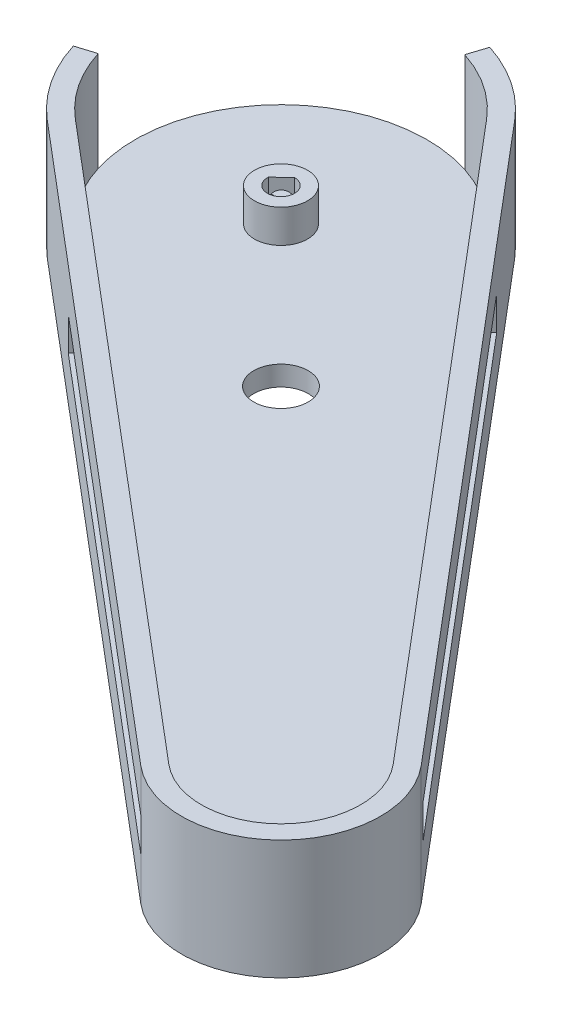
SolidWorks part; units mm, degrees
ref_plane "前视基准面" through (0, 0, 0) normal (0, 0, 1) x (1, 0, 0)
ref_plane "上视基准面" through (0, 0, 0) normal (0, 1, 0) x (1, 0, 0)
ref_plane "右视基准面" through (0, 0, 0) normal (1, 0, 0) x (0, 0, -1)
other "Configuration Table"
sketch "草图2" plane through (0, 0, 0) normal (0, 1, 0) x (1, 0, 0)
  line L0 (-140.5033, 0) -> (6884.6605, 0) construction
  line L1 (0, -140.5033) -> (0, 6884.6605) construction
  line L2 (0, 0) -> (42.4264, -42.4264)
  line L3 (42.4264, -42.4264) -> (-42.4264, 42.4264)
  line L4 (-58.5694, 23.3371) -> (32.7406, -53.88)
  line L5 (-23.3371, 58.5694) -> (53.88, -32.7406)
  circle A0 centre (-42.4264, 42.4264) radius 25
  circle A1 centre (42.4264, -42.4264) radius 15
  dimension "D3" = 50
  dimension "D4" = 30
  dimension "D1" = 60
  dimension "D2" = 120
extrude "凸台-拉伸2" add sketch "草图2" along normal blind 3
sketch "草图4" plane through (0, 3, 0) normal (0, 1, 0) x (1, 0, 0)
  line L0 (-58.5694, 23.3371) -> (32.7406, -53.88)
  line L1 (-58.5694, 23.3371) -> (32.7406, -53.88) construction
  line L2 (-23.3371, 58.5694) -> (53.88, -32.7406)
  line L3 (-23.3371, 58.5694) -> (53.88, -32.7406) construction
  line L4 (-56.6323, 25.6278) -> (34.6777, -51.5893)
  line L5 (-25.6278, 56.6323) -> (51.5893, -34.6777)
  circle A0 centre (-42.4264, 42.4264) radius 25
  circle A1 centre (42.4264, -42.4264) radius 15
  circle A2 centre (-42.4264, 42.4264) radius 22
  circle A3 centre (42.4264, -42.4264) radius 12
  circle A4 centre (-42.4264, 42.4264) radius 2.25
  circle A5 centre (42.4264, -42.4264) radius 2.5
  dimension "D3" = 4.5
  dimension "D4" = 5
  dimension "D1" = 3
  dimension "D2" = 3
extrude "切除-拉伸2" cut sketch "草图4" against normal through all contours A4 | A5
sketch "草图6" plane through (0, 3, 0) normal (0, 1, 0) x (1, 0, 0)
  circle A0 centre (-42.4264, 42.4264) radius 3.5
  dimension "D1" = 7
extrude "切除-拉伸3" cut sketch "草图6" against normal through all
sketch "草图7" plane through (0, 3, 0) normal (0, 1, 0) x (1, 0, 0)
  circle A0 centre (42.4264, -42.4264) radius 3.5
  dimension "D1" = 7
extrude "切除-拉伸4" cut sketch "草图7" against normal through all
sketch "草图8" plane through (0, 3, 0) normal (0, 1, 0) x (1, 0, 0)
  line L0 (-11.8521, 30.3069) -> (-26.8914, 12.9805)
  line L1 (-26.8914, 12.9805) -> (25.2188, -32.2512)
  line L2 (25.2188, -32.2512) -> (33.6267, -22.5647)
  line L3 (33.6267, -22.5647) -> (-15.703, 25.8704)
extrude "切除-拉伸5" cut sketch "草图8" against normal through all contours L2 L3 L0 L1
sketch "草图9" plane through (0, 3, 0) normal (0, 1, 0) x (1, 0, 0)
  line L0 (-23.3371, 58.5694) -> (53.88, -32.7406)
  line L1 (-58.5694, 23.3371) -> (32.7406, -53.88)
  line L2 (-56.6323, 25.6278) -> (34.6777, -51.5893)
  line L3 (-25.6278, 56.6323) -> (51.5893, -34.6777)
  circle A0 centre (-42.4264, 42.4264) radius 25
  circle A1 centre (42.4264, -42.4264) radius 15
  circle A2 centre (-42.4264, 42.4264) radius 22
  circle A3 centre (42.4264, -42.4264) radius 12
  line M8 (-58.5694, 23.3371) -> (32.7406, -53.88)
  arc M9 (32.7406, -53.88) -> (53.88, -32.7406) centre (42.4264, -42.4264) ccw
  line M10 (53.88, -32.7406) -> (-23.3371, 58.5694)
  arc M11 (-23.3371, 58.5694) -> (-58.5694, 23.3371) centre (-42.4264, 42.4264) ccw
  dimension "D1" = 3
  dimension "D2" = 3
extrude "凸台-拉伸4" add sketch "草图9" along normal blind 15 contours A2 L3 A0 L2 M11 | A1 A0 L3 M10 | A1 L2 A0 M8 | A3 L2 A1 L3 M9
sketch "草图10" plane through (0, 3, 0) normal (0, 1, 0) x (1, 0, 0)
  line L0 (-42.4264, 42.4264) -> (42.4264, -42.4264)
  line L1 (42.4264, -42.4264) -> (10.5288, -10.5288)
  line L2 (-26.8914, 12.9805) -> (-15.703, 25.8704)
  line L3 (-15.703, 25.8704) -> (33.6267, -22.5647)
  line L4 (33.6267, -22.5647) -> (25.2188, -32.2512)
  line L5 (25.2188, -32.2512) -> (-26.8914, 12.9805)
  line M5 (33.6267, -22.5647) -> (25.2188, -32.2512)
  line M6 (25.2188, -32.2512) -> (-26.8914, 12.9805)
  line M7 (-26.8914, 12.9805) -> (-15.703, 25.8704)
  line M8 (-15.703, 25.8704) -> (33.6267, -22.5647)
extrude "凸台-拉伸5" add sketch "草图10" against normal blind 3 contours L0 M7 M6 M5 | L0 M7 M5 M8
sketch "草图11" plane through (0, 3, 0) normal (0, 1, 0) x (1, 0, 0)
  line L0 (-42.4264, 42.4264) -> (42.4264, -42.4264)
  line L1 (42.4264, -42.4264) -> (-21.2132, 21.2132)
  circle A0 centre (-21.2132, 21.2132) radius 4.1
  circle A2 centre (42.4264, -42.4264) radius 4.1
  dimension "D3" = 8.2
  dimension "D4" = 8.2
  dimension "D1" = 120
  dimension "D2" = 90
extrude "切除-拉伸6" cut sketch "草图11" against normal blind 3
sketch "草图13" plane through (0, 3, 0) normal (0, 1, 0) x (1, 0, 0)
  circle A0 centre (-42.4264, 42.4264) radius 3.5
extrude "凸台-拉伸6" add sketch "草图13" against normal blind 3
sketch "草图14" plane through (0, 3, 0) normal (0, 1, 0) x (1, 0, 0)
  line L0 (-21.2132, 21.2132) -> (42.4264, -42.4264)
  line L1 (42.4264, -42.4264) -> (-42.4264, 42.4264)
  circle A0 centre (-42.4264, 42.4264) radius 2.05
  dimension "D2" = 4.1
  dimension "D1" = 120
extrude "凸台-拉伸7" add sketch "草图14" along normal blind 5
sketch "草图15" plane through (0, 8, 0) normal (0, 1, 0) x (1, 0, 0)
  circle A0 centre (-42.4264, 42.4264) radius 2.05
  circle A1 centre (-42.4264, 42.4264) radius 4
  dimension "D1" = 8
extrude "凸台-拉伸8" add sketch "草图15" against normal blind 5
sketch "草图17" plane through (0, 8, 0) normal (0, 1, 0) x (1, 0, 0)
  line L0 (-42.4264, 42.4264) -> (-59.3129, 60.8613)
  line L1 (-42.4264, 42.4264) -> (-43.4396, 43.5325)
  line L2 (-43.4396, 43.5325) -> (-40.1632, 46.5337)
  line L3 (-40.1632, 46.5337) -> (-45.1622, 41.9546)
  circle A0 centre (-42.4264, 42.4264) radius 2.05
  arc A1 (-23.3371, 58.5694) -> (-58.5694, 23.3371) centre (-42.4264, 42.4264) ccw construction
  dimension "D1" = 4.1
  dimension "D2" = 1.5
extrude "切除-拉伸7" cut sketch "草图17" against normal through all
sketch "草图18" plane through (-41.5018, 0, -45.3075) normal (0.6755, 0, 0.7374) x (0.7374, 0, -0.6755)
  line L0 (-1.2305, 0) -> (-4.0252, 0)
  line L1 (-2.6278, 0) -> (-2.6278, 4.9532)
  circle A0 centre (-2.6278, 4.9532) radius 1.3973
extrude "切除-拉伸8" cut sketch "草图18" against normal through all contours A0
sketch "草图19" plane through (0, 3, 0) normal (0, 1, 0) x (1, 0, 0)
  line L0 (-42.4264, 42.4264) -> (-66.2933, 34.9851)
  line L1 (-66.2933, 34.9851) -> (-34.7351, 66.2139)
  line L2 (-34.7351, 66.2139) -> (-42.4264, 42.4264)
  circle A0 centre (-42.4264, 42.4264) radius 22
  circle A1 centre (-42.4264, 42.4264) radius 25
extrude "切除-拉伸9" cut sketch "草图19" against normal through all both and the other way through all
sketch "草图20" plane through (-12.9144, 0, 15.2715) normal (-0.6457, 0, 0.7636) x (0.7636, 0, 0.6457)
  line L0 (-32.9451, 18) -> (-32.9451, 0)
  line L1 (-59.7913, 18) -> (59.7913, 18) construction
  line L2 (-59.7913, 0) -> (59.7913, 0) construction
  line L3 (-32.9451, 0) -> (59.7913, 0)
  line L4 (59.7913, 0) -> (59.7913, 18)
  line L5 (59.7913, 18) -> (-32.9451, 18)
  line L6 (-32.9451, 9) -> (59.7913, 9)
  line L7 (-32.9451, 6.5) -> (59.7913, 6.5)
  line L8 (-32.9451, 11.6) -> (59.7913, 11.6)
  dimension "D1" = 2.5
  dimension "D2" = 2.6
extrude "切除-拉伸11" cut sketch "草图20" against normal through all both and the other way through all contours L8 L0 L6 L4 | L0 L7 L4 L6
sketch "草图21" plane through (0, 0, 0) normal (0, -1, 0) x (1, 0, 0)
  line L0 (-21.2132, -21.2132) -> (42.4264, 42.4264)
  line L1 (42.4264, 42.4264) -> (-10.3418, -10.3418)
